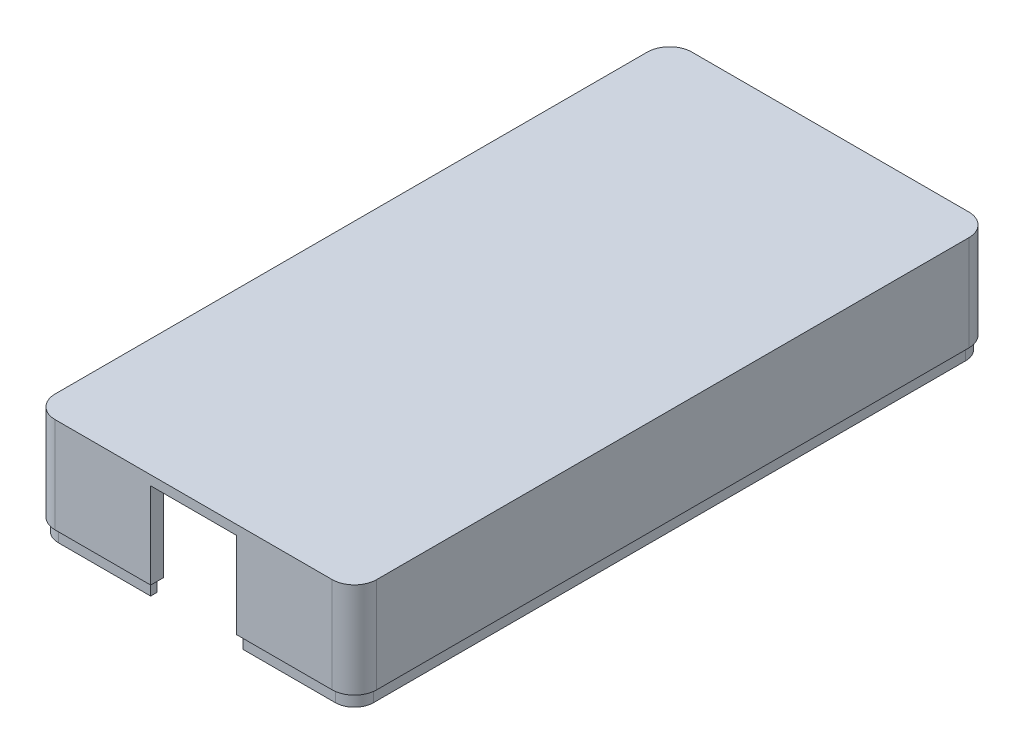
SolidWorks part; units mm, degrees
ref_plane "Alzado" through (0, 0, 0) normal (0, 0, 1) x (1, 0, 0)
ref_plane "Planta" through (0, 0, 0) normal (0, 1, 0) x (1, 0, 0)
ref_plane "Vista lateral" through (0, 0, 0) normal (1, 0, 0) x (0, 0, -1)
sketch "Sketch1" plane through (0, 0, 0) normal (0, 1, 0) x (1, 0, 0)
  line L1 (-21.75, -50) -> (21.75, -50)
  line L2 (-25.25, -46.5) -> (-25.25, 46.5)
  line L3 (-21.75, 50) -> (21.75, 50)
  line L4 (25.25, -46.5) -> (25.25, 46.5)
  line L5 (-25.25, -50) -> (25.25, 50) construction
  line L6 (-25.25, 50) -> (25.25, -50) construction
  arc A0 (-21.75, -50) -> (-25.25, -46.5) centre (-21.75, -46.5) cw
  arc A1 (21.75, -50) -> (25.25, -46.5) centre (21.75, -46.5) ccw
  arc A2 (-25.25, 46.5) -> (-21.75, 50) centre (-21.75, 46.5) cw
  arc A3 (21.75, 50) -> (25.25, 46.5) centre (21.75, 46.5) cw
  point P0 (0, 0)
  dimension "D3" = 3.5
  dimension "D1" = 50.5
  dimension "D2" = 100
extrude "Boss-Extrude1" add sketch "Sketch1" along normal blind 15
sketch "Sketch2" plane through (0, 0, 0) normal (0, -1, 0) x (1, 0, 0)
  line L0 (25.25, 46.5) -> (25.25, -46.5) construction
  line L1 (-19.75, -48) -> (19.75, -48)
  line L2 (-23.25, -44.5) -> (-23.25, 44.5)
  line L3 (-19.75, 48) -> (19.75, 48)
  line L4 (23.25, -44.5) -> (23.25, 44.5)
  line L5 (-23.25, -48) -> (23.25, 48) construction
  line L6 (-23.25, 48) -> (23.25, -48) construction
  line L7 (-21.75, 50) -> (21.75, 50) construction
  arc A0 (19.75, -48) -> (23.25, -44.5) centre (19.75, -44.5) ccw
  arc A1 (-19.75, -48) -> (-23.25, -44.5) centre (-19.75, -44.5) cw
  arc A2 (-23.25, 44.5) -> (-19.75, 48) centre (-19.75, 44.5) cw
  arc A3 (19.75, 48) -> (23.25, 44.5) centre (19.75, 44.5) cw
  point P0 (0, 0)
  dimension "D3" = 3.5
  dimension "D1" = 2
  dimension "D2" = 2
extrude "Cut-Extrude1" cut sketch "Sketch2" against normal blind 13.5
sketch "Sketch3" plane through (0, 0, 50) normal (0, 0, 1) x (1, 0, 0)
  line L0 (0, 0) -> (0, 15) construction
  line L1 (-21.75, 15) -> (21.75, 15) construction
  line L3 (-6.75, 13.5) -> (6.75, 13.5)
  line L4 (-6.75, 13.5) -> (-6.75, -13.5)
  line L5 (-6.75, -13.5) -> (6.75, -13.5)
  line L6 (6.75, 13.5) -> (6.75, -13.5)
  line L7 (-6.75, 13.5) -> (6.75, -13.5) construction
  line L8 (-6.75, -13.5) -> (6.75, 13.5) construction
  dimension "D1" = 1.5
  dimension "D2" = 13.5
extrude "Cut-Extrude2" cut sketch "Sketch3" against normal blind 15
curve "CurvaComp1"
curve "CurvaComp2"
sketch "Croquis2" plane through (0, 0, 0) normal (0, -1, 0) x (1, 0, 0)
  line L0 (-6.75, 50) -> (-6.75, 48) construction
  line L1 (-6.75, 50) -> (-6.75, 48)
  line L4 (-21.75, 50) -> (-6.75, 50) construction
  line L5 (-25.25, -46.5) -> (-25.25, 46.5) construction
  line L6 (21.75, -50) -> (-21.75, -50) construction
  line L7 (25.25, 46.5) -> (25.25, -46.5) construction
  line L8 (6.75, 50) -> (21.75, 50) construction
  line L9 (-21.75, 50) -> (-6.75, 50)
  line L10 (-25.25, -46.5) -> (-25.25, 46.5)
  line L11 (21.75, -50) -> (-21.75, -50)
  line L12 (25.25, 46.5) -> (25.25, -46.5)
  line L13 (6.75, 50) -> (21.75, 50)
  line L14 (-19.75, 48) -> (-6.75, 48) construction
  line L15 (-23.25, -44.5) -> (-23.25, 44.5) construction
  line L16 (19.75, -48) -> (-19.75, -48) construction
  line L17 (23.25, 44.5) -> (23.25, -44.5) construction
  line L19 (-19.75, 48) -> (-6.75, 48)
  line L20 (-23.25, -44.5) -> (-23.25, 44.5)
  line L21 (19.75, -48) -> (-19.75, -48)
  line L22 (23.25, 44.5) -> (23.25, -44.5)
  line L24 (6.75, 48) -> (6.75, 50) construction
  line L25 (6.75, 48) -> (6.75, 50)
  line L26 (19.75, 48) -> (6.75, 48) construction
  line L27 (19.75, 48) -> (6.75, 48)
  arc A0 (-21.75, 50) -> (-25.25, 46.5) centre (-21.75, 46.5) ccw construction
  arc A1 (-25.25, -46.5) -> (-21.75, -50) centre (-21.75, -46.5) ccw construction
  arc A2 (21.75, -50) -> (25.25, -46.5) centre (21.75, -46.5) ccw construction
  arc A3 (25.25, 46.5) -> (21.75, 50) centre (21.75, 46.5) ccw construction
  arc A4 (-21.75, 50) -> (-25.25, 46.5) centre (-21.75, 46.5) ccw
  arc A5 (-25.25, -46.5) -> (-21.75, -50) centre (-21.75, -46.5) ccw
  arc A6 (21.75, -50) -> (25.25, -46.5) centre (21.75, -46.5) ccw
  arc A7 (25.25, 46.5) -> (21.75, 50) centre (21.75, 46.5) ccw
  arc A8 (-19.75, 48) -> (-23.25, 44.5) centre (-19.75, 44.5) ccw construction
  arc A9 (-23.25, -44.5) -> (-19.75, -48) centre (-19.75, -44.5) ccw construction
  arc A10 (19.75, -48) -> (23.25, -44.5) centre (19.75, -44.5) ccw construction
  arc A11 (23.25, 44.5) -> (19.75, 48) centre (19.75, 44.5) ccw construction
  arc A12 (-19.75, 48) -> (-23.25, 44.5) centre (-19.75, 44.5) ccw
  arc A13 (-23.25, -44.5) -> (-19.75, -48) centre (-19.75, -44.5) ccw
  arc A14 (19.75, -48) -> (23.25, -44.5) centre (19.75, -44.5) ccw
  arc A15 (23.25, 44.5) -> (19.75, 48) centre (19.75, 44.5) ccw
sketch "Croquis3" plane through (0, 0, 0) normal (0, -1, 0) x (1, 0, 0)
  line L12 (7.25, 48.5) -> (19.75, 48.5)
  line L13 (7.25, 48.5) -> (19.75, 48.5)
  line L14 (7.25, 49.5) -> (7.25, 48.5)
  line L15 (7.25, 49.5) -> (7.25, 48.5)
  line L24 (-24.75, 46.5) -> (-24.75, -46.5)
  line L25 (-7.25, 49.5) -> (-21.75, 49.5)
  line L26 (-7.25, 48.5) -> (-7.25, 49.5)
  line L27 (-19.75, 48.5) -> (-7.25, 48.5)
  line L28 (-23.75, -44.5) -> (-23.75, 44.5)
  line L29 (19.75, -48.5) -> (-19.75, -48.5)
  line L30 (23.75, 44.5) -> (23.75, -44.5)
  line L33 (21.75, 49.5) -> (7.25, 49.5)
  line L34 (24.75, -46.5) -> (24.75, 46.5)
  line L35 (-21.75, -49.5) -> (21.75, -49.5)
  line L36 (-24.75, 46.5) -> (-24.75, -46.5)
  line L37 (-7.25, 49.5) -> (-21.75, 49.5)
  line L38 (-7.25, 48.5) -> (-7.25, 49.5)
  line L39 (-19.75, 48.5) -> (-7.25, 48.5)
  line L40 (-23.75, -44.5) -> (-23.75, 44.5)
  line L41 (19.75, -48.5) -> (-19.75, -48.5)
  line L42 (23.75, 44.5) -> (23.75, -44.5)
  line L45 (21.75, 49.5) -> (7.25, 49.5)
  line L46 (24.75, -46.5) -> (24.75, 46.5)
  line L47 (-21.75, -49.5) -> (21.75, -49.5)
  arc A16 (-21.75, 49.5) -> (-24.75, 46.5) centre (-21.75, 46.5) ccw
  arc A17 (-19.75, 48.5) -> (-23.75, 44.5) centre (-19.75, 44.5) ccw
  arc A18 (-23.75, -44.5) -> (-19.75, -48.5) centre (-19.75, -44.5) ccw
  arc A19 (19.75, -48.5) -> (23.75, -44.5) centre (19.75, -44.5) ccw
  arc A20 (23.75, 44.5) -> (19.75, 48.5) centre (19.75, 44.5) ccw
  arc A21 (24.75, 46.5) -> (21.75, 49.5) centre (21.75, 46.5) ccw
  arc A22 (21.75, -49.5) -> (24.75, -46.5) centre (21.75, -46.5) ccw
  arc A23 (-24.75, -46.5) -> (-21.75, -49.5) centre (-21.75, -46.5) ccw
  arc A24 (-21.75, 49.5) -> (-24.75, 46.5) centre (-21.75, 46.5) ccw
  arc A25 (-19.75, 48.5) -> (-23.75, 44.5) centre (-19.75, 44.5) ccw
  arc A26 (-23.75, -44.5) -> (-19.75, -48.5) centre (-19.75, -44.5) ccw
  arc A27 (19.75, -48.5) -> (23.75, -44.5) centre (19.75, -44.5) ccw
  arc A28 (23.75, 44.5) -> (19.75, 48.5) centre (19.75, 44.5) ccw
  arc A29 (24.75, 46.5) -> (21.75, 49.5) centre (21.75, 46.5) ccw
  arc A30 (21.75, -49.5) -> (24.75, -46.5) centre (21.75, -46.5) ccw
  arc A31 (-24.75, -46.5) -> (-21.75, -49.5) centre (-21.75, -46.5) ccw
  dimension "D1" = 0.5
extrude "Saliente-Extruir1" add sketch "Croquis3" along normal blind 2
